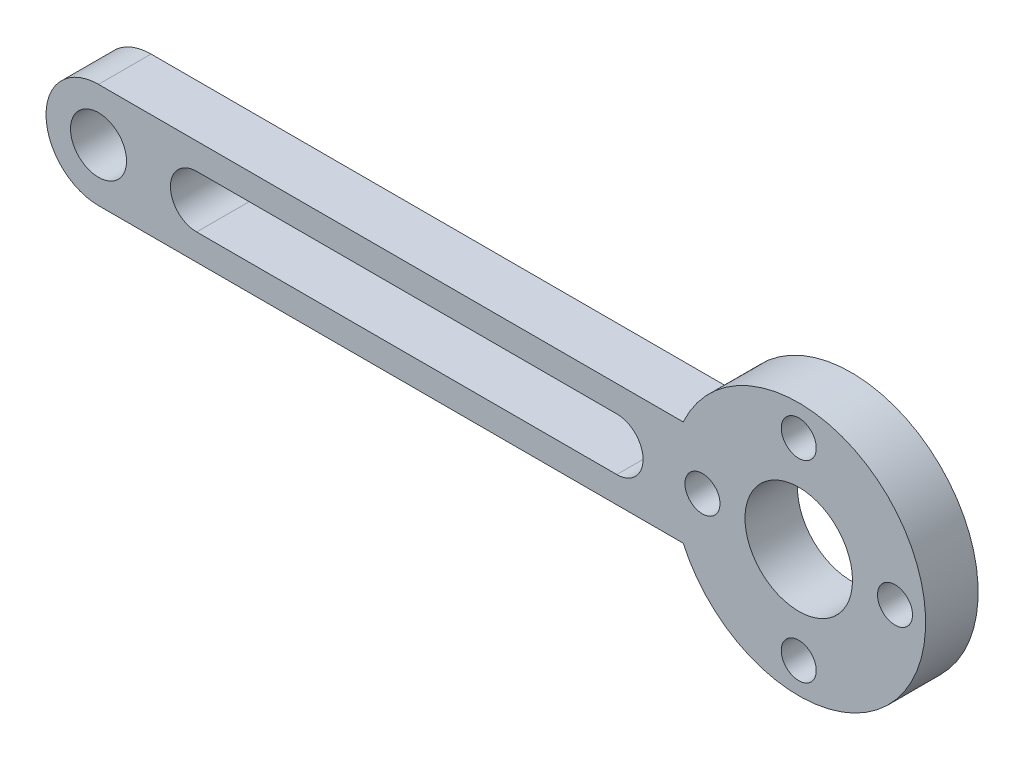
SolidWorks part; units mm, degrees
ref_plane "前视基准面" through (0, 0, 0) normal (0, 0, 1) x (1, 0, 0)
ref_plane "上视基准面" through (0, 0, 0) normal (0, 1, 0) x (1, 0, 0)
ref_plane "右视基准面" through (0, 0, 0) normal (1, 0, 0) x (0, 0, -1)
sketch "草图1" plane through (0, 0, 0) normal (0, 0, 1) x (1, 0, 0)
  line L0 (12, -5) -> (52, -5) construction
  line L3 (12, -8) -> (45.3998, -8)
  line L4 (12, -2) -> (45.3998, -2)
  line L5 (17.6072, -5) -> (41.6072, -5) construction
  line L6 (17.6072, -3.5) -> (41.6072, -3.5)
  line L7 (17.6072, -6.5) -> (41.6072, -6.5)
  arc A0 (12, -2) -> (12, -8) centre (12, -5) ccw
  circle A1 centre (12, -5) radius 1.6
  arc A3 (52, -12.25) -> (52, 2.25) centre (52, -5) ccw construction
  circle A4 centre (52, -5) radius 3.0712
  circle A5 centre (57.5, -5) radius 1
  circle A6 centre (46.5, -5) radius 1
  arc A7 (45.3998, -8) -> (45.3998, -2) centre (52, -5) ccw
  arc A8 (17.6072, -3.5) -> (17.6072, -6.5) centre (17.6072, -5) ccw
  arc A9 (41.6072, -6.5) -> (41.6072, -3.5) centre (41.6072, -5) ccw
  circle A10 centre (52, -10.5) radius 1
  circle A11 centre (46.5, -5) radius 1
  circle A12 centre (52, 0.5) radius 1
  point P17 (29.6072, -5)
  point P31 (52, -5)
  dimension "D1" = 6
  dimension "D2" = 3.2
  dimension "D3" = 7.25
  dimension "D5" = 2
  dimension "D7" = 2
  dimension "D8" = 5.5
  dimension "D9" = 24
  dimension "D4" = 40
  dimension "D6" = 5.5
  dimension "D10" = 3
  dimension "D11" = 4
extrude "凸台-拉伸2" add sketch "草图1" along normal blind 3 contours L3 A7 L4 A0 A12 A10 A9 L7 A8 L6 A1 A4 A5 A6
